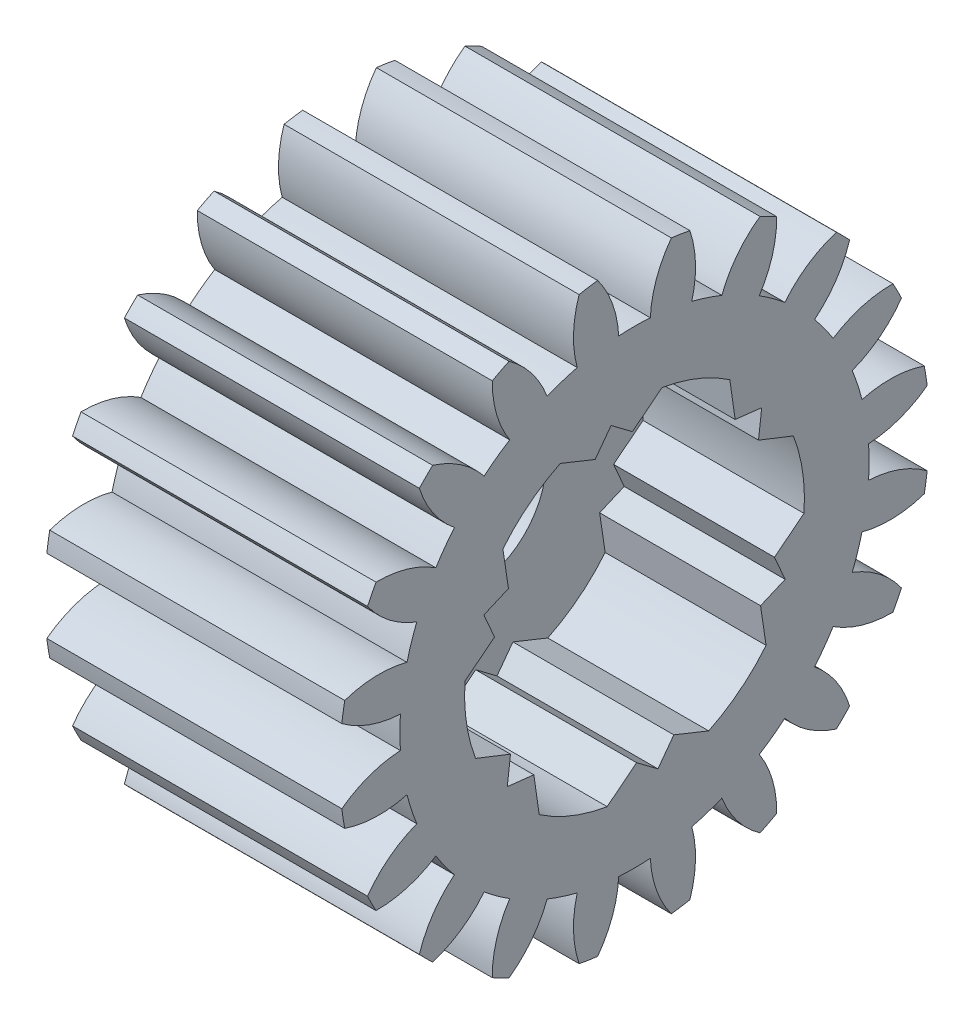
SolidWorks part; units mm, degrees
ref_plane "Plane1" through (0, 0, 0) normal (0, 0, 1) x (1, 0, 0)
ref_plane "Plane2" through (0, 0, 0) normal (0, 1, 0) x (1, 0, 0)
ref_plane "Plane3" through (0, 0, 0) normal (1, 0, 0) x (0, 0, -1)
other "Configuration Table"
sketch "HoldingSke" plane through (0, 0, 0) normal (0, 1, 0) x (1, 0, 0)
  line L0 (0, 0) -> (1.8794, -0.684)
  line L1 (-15, 0) -> (100, 0) construction
  line L2 (0, 0) -> (-2.1039, 2.3779)
  line L3 (0, 0) -> (-11.863, 4.5341)
  line L4 (0, 0) -> (8.1152, 2.9537)
  line L5 (0, 0) -> (-46.8476, -17.4728)
  line L6 (0, 0) -> (-1.6579, -1.1186)
  line L7 (-2.1039, 2.3779) -> (8.6588, 51.2067)
  line L8 (-76.2, 54.61) -> (-76.1, 54.61)
  line L9 (-67.7845, 28.3722) -> (-49.3413, 33.142)
  line L10 (-76.2, 71.12) -> (104.1128, 71.12)
  line L11 (0, 0) -> (-2, 0)
  line L12 (-76.2, 101.6) -> (-76.181, 101.6)
  line L13 (24.9733, 27.94) -> (52.9518, 28.4284)
  line L14 (24.9733, 27.94) -> (24.9743, 27.94)
  line L15 (24.9733, 27.94) -> (100.4006, 29.5858)
  line L16 (-63.627, -0.5) -> (-12.827, -0.5)
  circle A0 centre (0, 0) radius 0.5
  circle A1 centre (0, 0) radius 4.374
  circle A2 centre (0, 0) radius 37.5
  circle A3 centre (0, 0) radius 0.5
  dimension "MHD" = 8.748
  dimension "Hub_dia" = 75
  dimension "Bore" = 1
  dimension "MBD" = 1
  dimension "Num_teeth" = 20
  dimension "Pitch" = 2
  dimension "Overall_len" = 50
  dimension "Show_teeth" = 20
  dimension "Thickness" = 2
  dimension "OAL" = 50.0009
  dimension "T_dim" = 0.1
  dimension "Ap" = 14.5
  dimension "H" = 19.05
  dimension "Pitch_radius" = 180.3128
  dimension "Width" = 2
  dimension "Backlash" = 0.019
  dimension "Addendum_fac" = 1
  dimension "Dedendum_fac" = 1.25
  dimension "Clearance_fac" = 0.25
  dimension "Dedendum_add" = 0.001
  dimension "Module" = 0.5
sketch "BasProSke" plane through (0, 0, 0) normal (0, 1, 0) x (1, 0, 0)
  line L0 (-10, 0) -> (60, 0) construction
  line L1 (0, 0) -> (0, 5.5)
  line L2 (0, 0) -> (5.5, 0)
  line L3 (5.5, 0) -> (5.5, 5.5)
  line L4 (5.5, 5.5) -> (0, 5.5)
  dimension "Thickness" = 5.5
  dimension "Diameter" = 11
revolve "Base-Revolve" add sketch "BasProSke" angle 360 about L0
sketch "TooCutSke" plane through (0, 0, 0) normal (1, 0, 0) x (0, 0, -1)
  line L1 (0, 0) -> (0, 107) construction
  line L2 (0, 0) -> (-0.4255, 4.9819) construction
  line L3 (0, 0) -> (-1.5603, 9.8514) construction
  line L4 (-0.4255, 4.9819) -> (-0.7802, 4.9257) construction
  arc A0 (0.2947, 4.3641) -> (-0.2947, 4.3641) centre (0, 0) ccw
  arc A1 (0.7047, 5.4803) -> (-0.7047, 5.4803) centre (0, 0) ccw
  circle A2 centre (0, 0) radius 5 construction
  circle A3 centre (0, 0) radius 4.8407 construction
  arc A4 (-0.2947, 4.3641) -> (-0.7047, 5.4803) centre (-2.2921, 4.2637) ccw
  arc A5 (0.7047, 5.4803) -> (0.2947, 4.3641) centre (2.2921, 4.2637) ccw
  dimension "Root_dia" = 8.748
  dimension "Overcut_dia" = 11.0508
  dimension "Pitch_dia" = 10
  dimension "Base_dia" = 9.6815
  dimension "Flank_rad" = 2
  dimension "Half_ang" = 9
  dimension "Half_CT" = 0.359
extrude "ToothCut" cut sketch "TooCutSke" along normal through all
fillet "Breaks" [suppressed] radius 0.01
fillet "RootFillets" [suppressed] radius 0.126
pattern_circular "TeethCuts" count 20 every 18 about axis through (-10, 0, 0) along (1, 0, 0) of "ToothCut", "RootFillets", "Breaks"
sketch "HubNeaOneSke" plane through (0, 0, 0) normal (-1, 0, 0) x (0, 0, 1)
  circle A0 centre (0, 0) radius 4.374
  dimension "Diameter" = 8.748
extrude "HubNearOne" [suppressed] add sketch "HubNeaOneSke" along normal blind 44.5009
sketch "HubNeaBotSke" plane through (0, 0, 0) normal (-1, 0, 0) x (0, 0, 1)
  circle A0 centre (0, 0) radius 4.374
  dimension "Diameter" = 8.748
extrude "HubNearBoth" [suppressed] add sketch "HubNeaBotSke" along normal blind 22.2504
ref_plane "FarPln" through (5.5, 0, 0) normal (1, 0, 0) x (0, 0, -1)
sketch "HubFarSke" plane through (5.5, 0, 0) normal (1, 0, 0) x (0, 0, -1)
  circle A0 centre (0, 0) radius 4.374
  dimension "Diameter" = 8.748
extrude "HubFar" [suppressed] add sketch "HubFarSke" along normal blind 22.2504
sketch "BorSke" plane through (0, 0, 0) normal (1, 0, 0) x (0, 0, -1)
  circle A0 centre (0, 0) radius 0.5
  dimension "Diameter" = 1
extrude "Bore" cut sketch "BorSke" along normal mid plane 100.0017
sketch "KeySke" plane through (0, 0, 0) normal (1, 0, 0) x (0, 0, -1)
  line L0 (-0.05, 0) -> (-0.05, 0.6)
  line L1 (-0.05, 0.6) -> (0.05, 0.6)
  line L2 (0.05, 0.6) -> (0.05, 0)
  line L3 (0, 0) -> (0, 34) construction
  line L4 (-0.05, 0) -> (0.05, 0)
  dimension "Offset" = 0.6
  dimension "Width" = 0.1
extrude "Keyway" [suppressed] cut sketch "KeySke" along normal mid plane 100.0017
pattern_circular "Keyway2" [suppressed] count 2 every 90 about axis through (-10, 0, 0) along (1, 0, 0)
sketch "Sketch2" plane through (0, 0, 0) normal (-1, 0, 0) x (0, 0, 1)
  line L26 (-1.7772, 2.623) -> (-1.8763, 1.9301)
  line L27 (-2.3714, 1.8735) -> (-1.8763, 1.9301) construction
  line L28 (-1.8763, 1.9301) -> (-1.7772, 2.623) construction
  line L29 (-1.8763, 1.9301) -> (-2.3714, 1.8735)
  line L30 (-2.3714, 1.8735) -> (-2.3119, 1.3787)
  line L31 (-2.3119, 1.3787) -> (-2.9631, 1.122)
  line L32 (-0.5099, 3.1271) -> (0.0381, 2.6915)
  line L33 (0.0381, 2.6915) -> (0.4368, 2.9905)
  line L34 (0.4368, 2.9905) -> (0.7334, 2.5899)
  line L35 (0.7334, 2.5899) -> (1.383, 2.8506)
  line L36 (2.4532, 2.0051) -> (2.3499, 1.3128)
  line L37 (2.3499, 1.3128) -> (2.8082, 1.117) construction
  line L38 (2.3499, 1.3128) -> (2.8082, 1.117)
  line L39 (2.8082, 1.117) -> (2.6096, 0.6598)
  line L40 (2.6096, 0.6598) -> (3.1602, 0.2276)
  line L41 (1.7772, -2.623) -> (1.8763, -1.9301)
  line L42 (1.8763, -1.9301) -> (2.3714, -1.8735)
  line L43 (2.3714, -1.8735) -> (2.3119, -1.3787)
  line L44 (2.3119, -1.3787) -> (2.9631, -1.122)
  line L45 (0.5099, -3.1271) -> (-0.0381, -2.6915)
  line L46 (-0.0381, -2.6915) -> (-0.4368, -2.9905)
  line L47 (-0.4368, -2.9905) -> (-0.7334, -2.5899)
  line L48 (-0.7334, -2.5899) -> (-1.383, -2.8506)
  line L49 (-2.4532, -2.0051) -> (-2.3499, -1.3128)
  line L50 (-2.3499, -1.3128) -> (-2.8082, -1.117)
  line L51 (-2.8082, -1.117) -> (-2.6096, -0.6598)
  line L52 (-2.6096, -0.6598) -> (-3.1602, -0.2276)
  line L53 (2.9631, -1.122) -> (2.3119, -1.3787) construction
  arc A0 (1.383, 2.8506) -> (2.4532, 2.0051) centre (0, 0) cw
  arc A3 (3.1602, 0.2276) -> (2.9631, -1.122) centre (0, 0) cw
  arc A14 (1.7772, -2.623) -> (0.5099, -3.1271) centre (0, 0) cw
  arc A15 (-1.383, -2.8506) -> (-2.4532, -2.0051) centre (0, 0) cw
  arc A16 (-3.1602, -0.2276) -> (-2.9631, 1.122) centre (0, 0) cw
  arc A17 (-1.7772, 2.623) -> (-0.5099, 3.1271) centre (0, 0) cw
  arc A18 (-0.5099, 3.1271) -> (-1.7772, 2.623) centre (0, 0) ccw construction
  arc A19 (-2.9631, 1.122) -> (-3.1602, -0.2276) centre (0, 0) ccw construction
  arc A20 (-2.4532, -2.0051) -> (-1.383, -2.8506) centre (0, 0) ccw construction
  arc A21 (0.5099, -3.1271) -> (1.7772, -2.623) centre (0, 0) ccw construction
  arc A22 (2.9631, -1.122) -> (3.1602, 0.2276) centre (0, 0) ccw construction
  arc A23 (2.4532, 2.0051) -> (1.383, 2.8506) centre (0, 0) ccw construction
  point P43 (0, 0)
  dimension "D1" = 2
extrude "Cut-Extrude1" cut sketch "Sketch2" against normal through all both and the other way through all
sketch "Sketch3" plane through (0, 0, 0) normal (-1, 0, 0) x (0, 0, 1)
  circle A0 centre (0, 0) radius 3.65
  circle A1 centre (0, 0) radius 1.35
  dimension "D1" = 2.7
  dimension "D2" = 7.3
extrude "Boss-Extrude1" add sketch "Sketch3" against normal blind 2.5
equation "' \"Module@HoldingSke\" = 6.35"
equation "' \"Num_teeth@HoldingSke\" = 12"
equation "' \"Ap@HoldingSke\" =  20"
equation "' \"Ap@HoldingSke\" = 20"
equation "' \"Width@HoldingSke\" = 0.5 * 25.4"
equation "' \"Hub_dia@HoldingSke\"= 1 * 25.4"
equation "' \"Hub_dia@HoldingSke\" = 1 * 25.4"
equation "' \"Overall_len@HoldingSke\" = 1.0 * 25.4"
equation "' \"Bore@HoldingSke\" = 0.75 * 25.4"
equation "' \"T_dim@HoldingSke\" = 0.1 * 25.4"
equation "' \"Width@KeySke\" = 0.25 * 25.4"
equation "' \"Show_teeth@HoldingSke\" = 13"
equation "' \"Backlash@HoldingSke\" = 0.009 * 25.4"
equation "' \"Addendum_fac@HoldingSke\" = 1.0"
equation "' \"Dedendum_fac@HoldingSke\" = 1.25"
equation "' \"Dedendum_add@HoldingSke\" = 0.00005 * 25.4"
equation "' \"Clearance_fac@HoldingSke\" = 0.25"
equation "\"Pitch@HoldingSke\" = 1 / \"Module@HoldingSke\""
equation "\"Overcut_dia@TooCutSke\" = (\"Num_teeth@HoldingSke\" + 2 * \"Addendum_fac@HoldingSke\") / \"Pitch@HoldingSke\" + 0.002 * 25.4"
equation "\"Pitch_dia@TooCutSke\" = \"Num_teeth@HoldingSke\" / \"Pitch@HoldingSke\""
equation "\"Base_dia@TooCutSke\" = \"Num_teeth@HoldingSke\" / \"Pitch@HoldingSke\" * cos((\"Ap@HoldingSke\"  * 3.14159265 / 180))"
equation "\"Root_dia@TooCutSke\" = (\"Num_teeth@HoldingSke\" + 2) / \"Pitch@HoldingSke\" - 2 * (\"Addendum_fac@HoldingSke\" + \"Dedendum_fac@HoldingSke\") / \"Pitch@HoldingSke\" - \"Dedendum_add@HoldingSke\" * 2"
equation "\"Half_ang@TooCutSke\" = 180 / \"Num_teeth@HoldingSke\""
equation "\"Half_CT@TooCutSke\" = \"Num_teeth@HoldingSke\" / \"Pitch@HoldingSke\" * sin((3.14159265 / 2 / \"Num_teeth@HoldingSke\")) / 2 - 7 * \"Backlash@HoldingSke\" / 4"
equation "\"Flank_rad@TooCutSke\" = \"Num_teeth@HoldingSke\" / \"Pitch@HoldingSke\" / 5"
equation "\"Radius@RootFillets\" = \"Clearance_fac@HoldingSke\" / \"Pitch@HoldingSke\" + \"Dedendum_add@HoldingSke\""
equation "\"Break_rad@Breaks\" = 0.02 / \"Pitch@HoldingSke\""
equation "\"Thickness@HoldingSke\" = \"Width@HoldingSke\""
equation "\"OAL@HoldingSke\" = \"Thickness@HoldingSke\""
equation "\"MHD@HoldingSke\" = (\"Num_teeth@HoldingSke\" + 2) / \"Pitch@HoldingSke\" - 2 * (\"Addendum_fac@HoldingSke\" + \"Dedendum_fac@HoldingSke\")  / \"Pitch@HoldingSke\" - \"Dedendum_add@HoldingSke\" * 2"
equation "\"MBD@HoldingSke\" = (\"Num_teeth@HoldingSke\" + 2) / \"Pitch@HoldingSke\" - 2 * (\"Addendum_fac@HoldingSke\" + \"Dedendum_fac@HoldingSke\")  / \"Pitch@HoldingSke\" - \"Dedendum_add@HoldingSke\" * 2 - 0.002 * 25.4"
equation "\"MHD@HoldingSke\" = ((sgn( \"MHD@HoldingSke\" - \"Hub_dia@HoldingSke\" )-1)*( \"MHD@HoldingSke\" - \"Hub_dia@HoldingSke\" ))/-2+ \"Hub_dia@HoldingSke\""
equation "\"MBD@HoldingSke\" = ((sgn( \"MBD@HoldingSke\" - \"Bore@HoldingSke\" )-1)*( \"MBD@HoldingSke\" - \"Bore@HoldingSke\" ))/-2+ \"Bore@HoldingSke\""
equation "\"OAL@HoldingSke\" = ((sgn( \"OAL@HoldingSke\" - \"Overall_len@HoldingSke\" )+1)*( \"OAL@HoldingSke\" - \"Overall_len@HoldingSke\" ))/2 + \"Overall_len@HoldingSke\" + 0.000002 * 25.4"
equation "\"Num_teeth@TeethCuts\" = int( \"Show_teeth@HoldingSke\" ) + 1"
equation "\"Num_teeth@TeethCuts\" = ((sgn( \"Num_teeth@TeethCuts\" - \"Num_teeth@HoldingSke\" )-1)*( \"Num_teeth@TeethCuts\" - \"Num_teeth@HoldingSke\" ))/-2+ \"Num_teeth@HoldingSke\""
equation "\"Num_teeth@TeethCuts\" = ((sgn( \"Num_teeth@TeethCuts\" - 2.0)+1)*( \"Num_teeth@TeethCuts\" - 2.0))/2 +2.0"
equation "\"Angle@TeethCuts\" = 360.0 / \"Num_teeth@HoldingSke\""
equation "\"Diameter@BasProSke\" = (\"Num_teeth@HoldingSke\" + 2 * \"Addendum_fac@HoldingSke\") / \"Pitch@HoldingSke\""
equation "' \"Fillet_rad@BasProSke\" =  \"Thickness@HoldingSke\" * 0.05"
equation "' \"Fillet_rad@BasProSke\" = \"Thickness@HoldingSke\" * 0.05"
equation "\"MHD@HoldingSke\" = ((sgn( \"MHD@HoldingSke\" - \"Root_dia@TooCutSke\" )-1)*( \"MHD@HoldingSke\" - \"Root_dia@TooCutSke\" ))/-2+ \"Root_dia@TooCutSke\""
equation "\"Diameter@HubNeaOneSke\" = \"MHD@HoldingSke\""
equation "\"Length@HubNearOne\" = \"OAL@HoldingSke\" - \"Thickness@BasProSke\""
equation "\"Diameter@HubNeaBotSke\" = \"MHD@HoldingSke\""
equation "\"Length@HubNearBoth\" = ( \"OAL@HoldingSke\" - \"Thickness@BasProSke\" ) / 2.0"
equation "\"Thickness@FarPln\" = \"Thickness@BasProSke\""
equation "\"Diameter@HubFarSke\" = \"MHD@HoldingSke\""
equation "\"Length@HubFar\" = ( \"OAL@HoldingSke\" - \"Thickness@BasProSke\" ) / 2.0"
equation "\"Diameter@BorSke\" = \"MBD@HoldingSke\""
equation "\"D1@Bore\" = \"OAL@HoldingSke\" * 2.0"
equation "\"D1@Keyway\" = \"OAL@HoldingSke\" * 2.0"
equation "\"Offset@KeySke\" = \"T_dim@HoldingSke\" + \"MBD@HoldingSke\" / 2.0"
